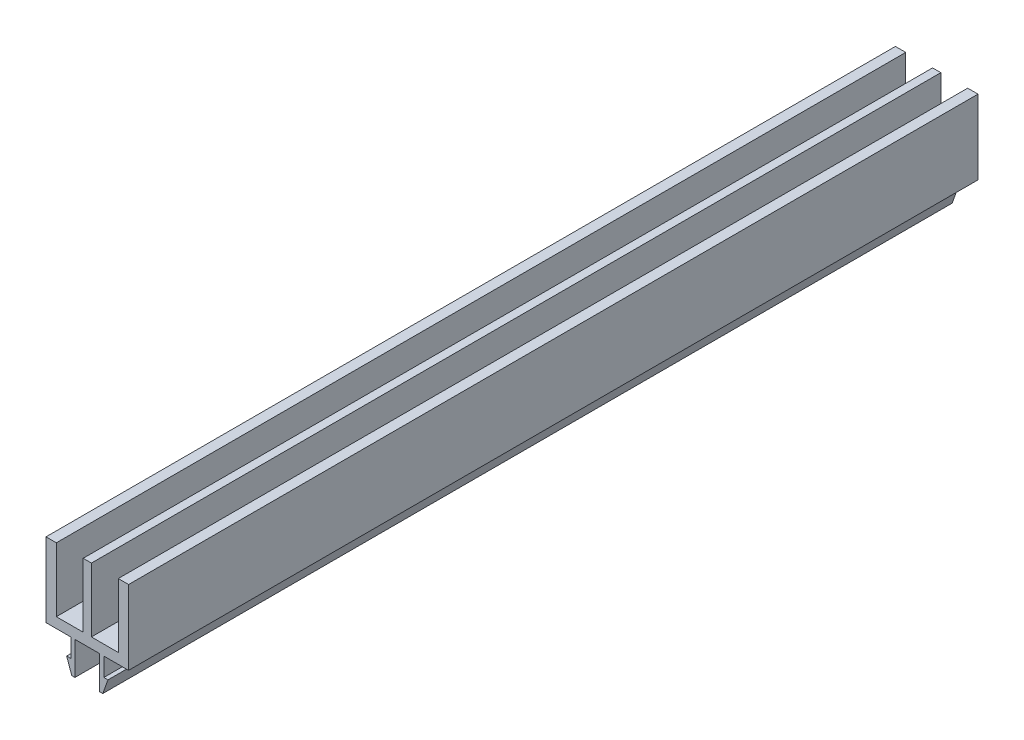
SolidWorks part; units mm, degrees
ref_plane "Plan de face" through (0, 0, 0) normal (0, 0, 1) x (1, 0, 0)
ref_plane "Plan de dessus" through (0, 0, 0) normal (0, 1, 0) x (1, 0, 0)
ref_plane "Plan de droite" through (0, 0, 0) normal (1, 0, 0) x (0, 0, -1)
ref_plane "Plan1" through (0, 0, 50) normal (0, 0, 1) x (1, 0, 0)
sketch "Esquisse1" plane through (0, 0, 50) normal (0, 0, 1) x (1, 0, 0)
  line L0 (-1, 2.5) -> (-7.5, 2.5)
  line L1 (-7.5, 2.5) -> (-7.5, 18)
  line L2 (-7.5, 18) -> (-10, 18)
  line L3 (-10, 18) -> (-10, 0)
  line L4 (-10, 0) -> (-4, 0)
  line L5 (-4, 0) -> (-4, -4.5)
  line L6 (-4, -4.5) -> (-5, -4.5)
  line L7 (-5, -4.5) -> (-3.75, -8)
  line L8 (-3.75, -8) -> (-3, -8)
  line L9 (-3, -8) -> (-3, 0)
  line L10 (-3, 0) -> (3, 0)
  line L11 (3, 0) -> (3, -8)
  line L12 (3, -8) -> (3.75, -8)
  line L13 (3.75, -8) -> (5, -4.5)
  line L14 (5, -4.5) -> (4, -4.5)
  line L15 (4, -4.5) -> (4, 0)
  line L16 (4, 0) -> (10, 0)
  line L17 (10, 0) -> (10, 18)
  line L18 (10, 18) -> (7.5, 18)
  line L19 (7.5, 18) -> (7.5, 2.5)
  line L20 (7.5, 2.5) -> (1, 2.5)
  line L21 (1, 2.5) -> (1, 18)
  line L22 (1, 18) -> (-1, 18)
  line L23 (-1, 18) -> (-1, 2.5)
extrude "Boss.-Extru.1" add sketch "Esquisse1" against normal blind 205.71
